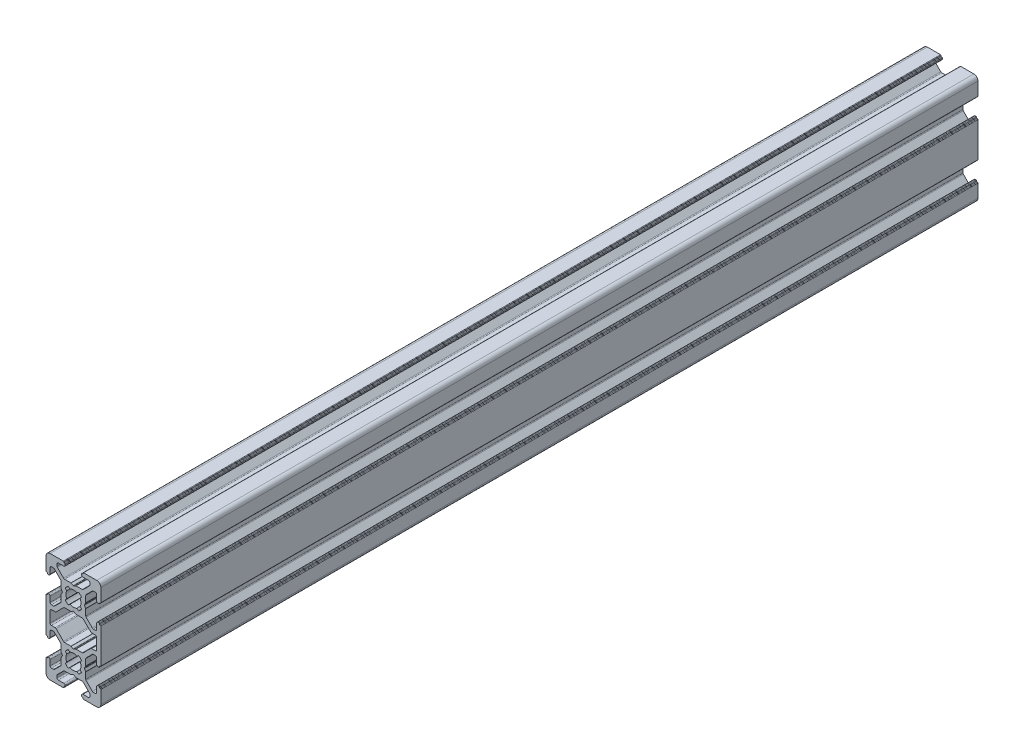
SolidWorks part; units mm, degrees
material "6063-T5"
ref_plane "前视基准面" through (0, 0, 0) normal (0, 0, 1) x (1, 0, 0)
ref_plane "上视基准面" through (0, 0, 0) normal (0, 1, 0) x (1, 0, 0)
ref_plane "右视基准面" through (0, 0, 0) normal (1, 0, 0) x (0, 0, -1)
ref_plane "基准面4" through (0, 0, 10) normal (0, 0, 1) x (1, 0, 0)
sketch "草图1" plane through (0, 0, 10) normal (0, 0, 1) x (1, 0, 0)
  line L0 (2.9477, 1.8871) -> (2.4453, 1.2582)
  line L1 (2.4453, -1.2582) -> (2.9477, -1.8871)
  line L2 (1.8871, -2.9477) -> (1.2582, -2.4453)
  line L3 (-1.2582, -2.4453) -> (-1.8871, -2.9477)
  line L4 (-2.9477, -1.8871) -> (-2.4453, -1.2582)
  line L5 (-2.4453, 1.2582) -> (-2.9477, 1.8871)
  line L6 (-1.8871, 2.9477) -> (-1.2582, 2.4453)
  line L7 (1.2582, 2.4453) -> (1.8871, 2.9477)
  line L8 (2.9477, -18.1129) -> (2.4453, -18.7418)
  line L9 (2.4453, -21.2582) -> (2.9477, -21.8871)
  line L10 (1.8871, -22.9477) -> (1.2582, -22.4453)
  line L11 (-1.2582, -22.4453) -> (-1.8871, -22.9477)
  line L12 (-2.9477, -21.8871) -> (-2.4453, -21.2582)
  line L13 (-2.4453, -18.7418) -> (-2.9477, -18.1129)
  line L14 (-1.8871, -17.0523) -> (-1.2582, -17.5547)
  line L15 (1.2582, -17.5547) -> (1.8871, -17.0523)
  line L16 (-0.9538, -15.4999) -> (-3.2324, -15.4999)
  line L17 (-3.586, -15.3534) -> (-6.2929, -12.6465)
  line L18 (-6.6464, -12.5) -> (-8, -12.5)
  line L19 (-8.5, -12) -> (-8.5, -8)
  line L20 (-8, -7.5) -> (-6.6464, -7.5)
  line L21 (-6.2929, -7.3536) -> (-3.5858, -4.6465)
  line L22 (-3.2322, -4.5) -> (-0.9536, -4.5)
  line L23 (-0.8536, -4.4732) -> (-0.1, -4.0381)
  line L24 (0.1, -4.0381) -> (0.8536, -4.4732)
  line L25 (0.9536, -4.5) -> (3.2322, -4.5)
  line L26 (3.5858, -4.6465) -> (6.2929, -7.3536)
  line L27 (6.6464, -7.5) -> (8, -7.5)
  line L28 (8.5, -8) -> (8.5, -12)
  line L29 (8, -12.5) -> (6.6464, -12.5)
  line L30 (6.2929, -12.6465) -> (3.586, -15.3534)
  line L31 (3.2324, -15.4999) -> (0.9538, -15.4999)
  line L32 (0.8538, -15.5267) -> (0.1, -15.9619)
  line L33 (-0.1, -15.9619) -> (-0.8538, -15.5267)
  line L34 (6, 8) -> (6, 7.2678)
  line L35 (5.8536, 6.9142) -> (3.5859, 4.6465)
  line L36 (3.2323, 4.5) -> (0.9537, 4.5)
  line L37 (0.8537, 4.4733) -> (0.1, 4.0381)
  line L38 (-0.1, 4.0381) -> (-0.8537, 4.4733)
  line L39 (-0.9537, 4.5) -> (-3.2323, 4.5)
  line L40 (-3.5859, 4.6465) -> (-5.8536, 6.9142)
  line L41 (-6, 7.2678) -> (-6, 8)
  line L42 (-5.5, 8.5) -> (-3.5, 8.5)
  line L43 (-3, 9) -> (-3, 9.3)
  line L44 (-3.2, 9.5) -> (-3.3, 9.5)
  line L45 (-3.5, 9.7) -> (-3.5, 9.8)
  line L46 (-3.7, 10) -> (-8.5, 10)
  line L47 (-10, 8.5) -> (-10, 3.7)
  line L48 (-9.8, 3.5) -> (-9.7, 3.5)
  line L49 (-9.5, 3.3) -> (-9.5, 3.2)
  line L50 (-9.3, 3) -> (-9, 3)
  line L51 (-8.5, 3.5) -> (-8.5, 5.55)
  line L52 (-8, 6.05) -> (-7.3178, 6.05)
  line L53 (-6.9642, 5.9036) -> (-4.6464, 3.5858)
  line L54 (-4.5, 3.2322) -> (-4.5, 0.9536)
  line L55 (-4.4732, 0.8536) -> (-4.0381, 0.1)
  line L56 (-4.0381, -0.1) -> (-4.4732, -0.8536)
  line L57 (-4.5, -0.9536) -> (-4.5, -3.2322)
  line L58 (-4.6464, -3.5858) -> (-6.8642, -5.8036)
  line L59 (-7.2178, -5.95) -> (-8, -5.95)
  line L60 (-8.5, -5.45) -> (-8.5, -3.5)
  line L61 (-9, -3) -> (-9.3, -3)
  line L62 (-9.5, -3.2) -> (-9.5, -3.3)
  line L63 (-9.7, -3.5) -> (-9.8, -3.5)
  line L64 (-10, -3.7) -> (-10, -16.35)
  line L65 (-9.8, -16.55) -> (-9.7, -16.55)
  line L66 (-9.5, -16.75) -> (-9.5, -16.85)
  line L67 (-9.3, -17.05) -> (-9, -17.05)
  line L68 (-8.5, -16.55) -> (-8.5, -14.5)
  line L69 (-8, -14) -> (-7.2678, -14)
  line L70 (-6.9142, -14.1464) -> (-4.6464, -16.4142)
  line L71 (-4.5, -16.7678) -> (-4.5, -19.0464)
  line L72 (-4.4732, -19.1464) -> (-4.0381, -19.9)
  line L73 (-4.0381, -20.1) -> (-4.4732, -20.8536)
  line L74 (-4.5, -20.9536) -> (-4.5, -23.2322)
  line L75 (-4.6464, -23.5858) -> (-6.9142, -25.8536)
  line L76 (-7.2678, -26) -> (-8, -26)
  line L77 (-8.5, -25.5) -> (-8.5, -23.55)
  line L78 (-9, -23.05) -> (-9.3, -23.05)
  line L79 (-9.5, -23.25) -> (-9.5, -23.35)
  line L80 (-9.7, -23.55) -> (-9.8, -23.55)
  line L81 (-10, -23.75) -> (-10, -28.5)
  line L82 (-8.5, -30) -> (-3.7, -30)
  line L83 (-3.5, -29.8) -> (-3.5, -29.7)
  line L84 (-3.3, -29.5) -> (-3.2, -29.5)
  line L85 (-3, -29.3) -> (-3, -29)
  line L86 (-3.5, -28.5) -> (-5.5, -28.5)
  line L87 (-6, -28) -> (-6, -27.2678)
  line L88 (-5.8536, -26.9142) -> (-3.5858, -24.6464)
  line L89 (-3.2322, -24.5) -> (-0.9536, -24.5)
  line L90 (-0.8536, -24.4732) -> (-0.1, -24.0381)
  line L91 (0.1, -24.0381) -> (0.8536, -24.4732)
  line L92 (0.9536, -24.5) -> (3.2322, -24.5)
  line L93 (3.5858, -24.6464) -> (5.8536, -26.9142)
  line L94 (6, -27.2678) -> (6, -28)
  line L95 (5.5, -28.5) -> (3.5, -28.5)
  line L96 (3, -29) -> (3, -29.3)
  line L97 (3.2, -29.5) -> (3.3, -29.5)
  line L98 (3.5, -29.7) -> (3.5, -29.8)
  line L99 (3.7, -30) -> (8.5, -30)
  line L100 (10, -28.5) -> (10, -23.75)
  line L101 (9.8, -23.55) -> (9.7, -23.55)
  line L102 (9.5, -23.35) -> (9.5, -23.25)
  line L103 (9.3, -23.05) -> (9, -23.05)
  line L104 (8.5, -23.55) -> (8.5, -25.5)
  line L105 (8, -26) -> (7.2678, -26)
  line L106 (6.9142, -25.8536) -> (4.6464, -23.5858)
  line L107 (4.5, -23.2322) -> (4.5, -20.9536)
  line L108 (4.4732, -20.8536) -> (4.0381, -20.1)
  line L109 (4.0381, -19.9) -> (4.4732, -19.1464)
  line L110 (4.5, -19.0464) -> (4.5, -16.7678)
  line L111 (4.6464, -16.4142) -> (6.9142, -14.1464)
  line L112 (7.2678, -14) -> (8, -14)
  line L113 (8.5, -14.5) -> (8.5, -16.55)
  line L114 (9, -17.05) -> (9.3, -17.05)
  line L115 (9.5, -16.85) -> (9.5, -16.75)
  line L116 (9.7, -16.55) -> (9.8, -16.55)
  line L117 (10, -16.35) -> (10, -3.7)
  line L118 (9.8, -3.5) -> (9.7, -3.5)
  line L119 (9.5, -3.3) -> (9.5, -3.2)
  line L120 (9.3, -3) -> (9, -3)
  line L121 (8.5, -3.5) -> (8.5, -5.5)
  line L122 (8, -6) -> (7.2678, -6)
  line L123 (6.9142, -5.8536) -> (4.6464, -3.5858)
  line L124 (4.5, -3.2322) -> (4.5, -0.9536)
  line L125 (4.4732, -0.8536) -> (4.0381, -0.1)
  line L126 (4.0381, 0.1) -> (4.4732, 0.8536)
  line L127 (4.5, 0.9536) -> (4.5, 3.2322)
  line L128 (4.6464, 3.5858) -> (6.9142, 5.8536)
  line L129 (7.2678, 6) -> (8, 6)
  line L130 (8.5, 5.5) -> (8.5, 3.5)
  line L131 (9, 3) -> (9.3, 3)
  line L132 (9.5, 3.2) -> (9.5, 3.3)
  line L133 (9.7, 3.5) -> (9.8, 3.5)
  line L134 (10, 3.7) -> (10, 8.5)
  line L135 (8.5, 10) -> (3.7, 10)
  line L136 (3.5, 9.8) -> (3.5, 9.7)
  line L137 (3.3, 9.5) -> (3.2, 9.5)
  line L138 (3, 9.3) -> (3, 9)
  line L139 (3.5, 8.5) -> (5.5, 8.5)
  arc A0 (2.4453, 1.2582) -> (2.4453, -1.2582) centre (0, 0) cw
  arc A1 (2.9477, -1.8871) -> (1.8871, -2.9477) centre (0, 0) cw
  arc A2 (1.2582, -2.4453) -> (-1.2582, -2.4453) centre (0, 0) cw
  arc A3 (-1.8871, -2.9477) -> (-2.9477, -1.8871) centre (0, 0) cw
  arc A4 (-2.4453, -1.2582) -> (-2.4453, 1.2582) centre (0, 0) cw
  arc A5 (-2.9477, 1.8871) -> (-1.8871, 2.9477) centre (0, 0) cw
  arc A6 (-1.2582, 2.4453) -> (1.2582, 2.4453) centre (0, 0) cw
  arc A7 (1.8871, 2.9477) -> (2.9477, 1.8871) centre (0, 0) cw
  arc A8 (2.4453, -18.7418) -> (2.4453, -21.2582) centre (0, -20) cw
  arc A9 (2.9477, -21.8871) -> (1.8871, -22.9477) centre (0, -20) cw
  arc A10 (1.2582, -22.4453) -> (-1.2582, -22.4453) centre (0, -20) cw
  arc A11 (-1.8871, -22.9477) -> (-2.9477, -21.8871) centre (0, -20) cw
  arc A12 (-2.4453, -21.2582) -> (-2.4453, -18.7418) centre (0, -20) cw
  arc A13 (-2.9477, -18.1129) -> (-1.8871, -17.0523) centre (0, -20) cw
  arc A14 (-1.2582, -17.5547) -> (1.2582, -17.5547) centre (0, -20) cw
  arc A15 (1.8871, -17.0523) -> (2.9477, -18.1129) centre (0, -20) cw
  arc A16 (-0.8538, -15.5267) -> (-0.9538, -15.4999) centre (-0.9538, -15.6999) ccw
  arc A17 (-3.2324, -15.4999) -> (-3.586, -15.3534) centre (-3.2324, -14.9999) cw
  arc A18 (-6.2929, -12.6465) -> (-6.6464, -12.5) centre (-6.6464, -13) ccw
  arc A19 (-8, -12.5) -> (-8.5, -12) centre (-8, -12) cw
  arc A20 (-8.5, -8) -> (-8, -7.5) centre (-8, -8) cw
  arc A21 (-6.6464, -7.5) -> (-6.2929, -7.3536) centre (-6.6464, -7) ccw
  arc A22 (-3.5858, -4.6465) -> (-3.2322, -4.5) centre (-3.2322, -5) cw
  arc A23 (-0.9536, -4.5) -> (-0.8536, -4.4732) centre (-0.9536, -4.3) ccw
  arc A24 (-0.1, -4.0381) -> (0.1, -4.0381) centre (0, -4.2113) cw
  arc A25 (0.8536, -4.4732) -> (0.9536, -4.5) centre (0.9536, -4.3) ccw
  arc A26 (3.2322, -4.5) -> (3.5858, -4.6465) centre (3.2322, -5) cw
  arc A27 (6.2929, -7.3536) -> (6.6464, -7.5) centre (6.6464, -7) ccw
  arc A28 (8, -7.5) -> (8.5, -8) centre (8, -8) cw
  arc A29 (8.5, -12) -> (8, -12.5) centre (8, -12) cw
  arc A30 (6.6464, -12.5) -> (6.2929, -12.6465) centre (6.6464, -13) ccw
  arc A31 (3.586, -15.3534) -> (3.2324, -15.4999) centre (3.2324, -14.9999) cw
  arc A32 (0.9538, -15.4999) -> (0.8538, -15.5267) centre (0.9538, -15.6999) ccw
  arc A33 (0.1, -15.9619) -> (-0.1, -15.9619) centre (0, -15.7887) cw
  arc A34 (5.5, 8.5) -> (6, 8) centre (5.5, 8) cw
  arc A35 (6, 7.2678) -> (5.8536, 6.9142) centre (5.5, 7.2678) cw
  arc A36 (3.5859, 4.6465) -> (3.2323, 4.5) centre (3.2323, 5) cw
  arc A37 (0.9537, 4.5) -> (0.8537, 4.4733) centre (0.9537, 4.3) ccw
  arc A38 (0.1, 4.0381) -> (-0.1, 4.0381) centre (0, 4.2113) cw
  arc A39 (-0.8537, 4.4733) -> (-0.9537, 4.5) centre (-0.9537, 4.3) ccw
  arc A40 (-3.2323, 4.5) -> (-3.5859, 4.6465) centre (-3.2323, 5) cw
  arc A41 (-5.8536, 6.9142) -> (-6, 7.2678) centre (-5.5, 7.2678) cw
  arc A42 (-6, 8) -> (-5.5, 8.5) centre (-5.5, 8) cw
  arc A43 (-3.5, 8.5) -> (-3, 9) centre (-3.5, 9) ccw
  arc A44 (-3, 9.3) -> (-3.2, 9.5) centre (-3.2, 9.3) ccw
  arc A45 (-3.3, 9.5) -> (-3.5, 9.7) centre (-3.3, 9.7) cw
  arc A46 (-3.5, 9.8) -> (-3.7, 10) centre (-3.7, 9.8) ccw
  arc A47 (-8.5, 10) -> (-10, 8.5) centre (-8.5, 8.5) ccw
  arc A48 (-10, 3.7) -> (-9.8, 3.5) centre (-9.8, 3.7) ccw
  arc A49 (-9.7, 3.5) -> (-9.5, 3.3) centre (-9.7, 3.3) cw
  arc A50 (-9.5, 3.2) -> (-9.3, 3) centre (-9.3, 3.2) ccw
  arc A51 (-9, 3) -> (-8.5, 3.5) centre (-9, 3.5) ccw
  arc A52 (-8.5, 5.55) -> (-8, 6.05) centre (-8, 5.55) cw
  arc A53 (-7.3178, 6.05) -> (-6.9642, 5.9036) centre (-7.3178, 5.55) cw
  arc A54 (-4.6464, 3.5858) -> (-4.5, 3.2322) centre (-5, 3.2322) cw
  arc A55 (-4.5, 0.9536) -> (-4.4732, 0.8536) centre (-4.3, 0.9536) ccw
  arc A56 (-4.0381, 0.1) -> (-4.0381, -0.1) centre (-4.2113, 0) cw
  arc A57 (-4.4732, -0.8536) -> (-4.5, -0.9536) centre (-4.3, -0.9536) ccw
  arc A58 (-4.5, -3.2322) -> (-4.6464, -3.5858) centre (-5, -3.2322) cw
  arc A59 (-6.8642, -5.8036) -> (-7.2178, -5.95) centre (-7.2178, -5.45) cw
  arc A60 (-8, -5.95) -> (-8.5, -5.45) centre (-8, -5.45) cw
  arc A61 (-8.5, -3.5) -> (-9, -3) centre (-9, -3.5) ccw
  arc A62 (-9.3, -3) -> (-9.5, -3.2) centre (-9.3, -3.2) ccw
  arc A63 (-9.5, -3.3) -> (-9.7, -3.5) centre (-9.7, -3.3) cw
  arc A64 (-9.8, -3.5) -> (-10, -3.7) centre (-9.8, -3.7) ccw
  arc A65 (-10, -16.35) -> (-9.8, -16.55) centre (-9.8, -16.35) ccw
  arc A66 (-9.7, -16.55) -> (-9.5, -16.75) centre (-9.7, -16.75) cw
  arc A67 (-9.5, -16.85) -> (-9.3, -17.05) centre (-9.3, -16.85) ccw
  arc A68 (-9, -17.05) -> (-8.5, -16.55) centre (-9, -16.55) ccw
  arc A69 (-8.5, -14.5) -> (-8, -14) centre (-8, -14.5) cw
  arc A70 (-7.2678, -14) -> (-6.9142, -14.1464) centre (-7.2678, -14.5) cw
  arc A71 (-4.6464, -16.4142) -> (-4.5, -16.7678) centre (-5, -16.7678) cw
  arc A72 (-4.5, -19.0464) -> (-4.4732, -19.1464) centre (-4.3, -19.0464) ccw
  arc A73 (-4.0381, -19.9) -> (-4.0381, -20.1) centre (-4.2113, -20) cw
  arc A74 (-4.4732, -20.8536) -> (-4.5, -20.9536) centre (-4.3, -20.9536) ccw
  arc A75 (-4.5, -23.2322) -> (-4.6464, -23.5858) centre (-5, -23.2322) cw
  arc A76 (-6.9142, -25.8536) -> (-7.2678, -26) centre (-7.2678, -25.5) cw
  arc A77 (-8, -26) -> (-8.5, -25.5) centre (-8, -25.5) cw
  arc A78 (-8.5, -23.55) -> (-9, -23.05) centre (-9, -23.55) ccw
  arc A79 (-9.3, -23.05) -> (-9.5, -23.25) centre (-9.3, -23.25) ccw
  arc A80 (-9.5, -23.35) -> (-9.7, -23.55) centre (-9.7, -23.35) cw
  arc A81 (-9.8, -23.55) -> (-10, -23.75) centre (-9.8, -23.75) ccw
  arc A82 (-10, -28.5) -> (-8.5, -30) centre (-8.5, -28.5) ccw
  arc A83 (-3.7, -30) -> (-3.5, -29.8) centre (-3.7, -29.8) ccw
  arc A84 (-3.5, -29.7) -> (-3.3, -29.5) centre (-3.3, -29.7) cw
  arc A85 (-3.2, -29.5) -> (-3, -29.3) centre (-3.2, -29.3) ccw
  arc A86 (-3, -29) -> (-3.5, -28.5) centre (-3.5, -29) ccw
  arc A87 (-5.5, -28.5) -> (-6, -28) centre (-5.5, -28) cw
  arc A88 (-6, -27.2678) -> (-5.8536, -26.9142) centre (-5.5, -27.2678) cw
  arc A89 (-3.5858, -24.6464) -> (-3.2322, -24.5) centre (-3.2322, -25) cw
  arc A90 (-0.9536, -24.5) -> (-0.8536, -24.4732) centre (-0.9536, -24.3) ccw
  arc A91 (-0.1, -24.0381) -> (0.1, -24.0381) centre (0, -24.2113) cw
  arc A92 (0.8536, -24.4732) -> (0.9536, -24.5) centre (0.9536, -24.3) ccw
  arc A93 (3.2322, -24.5) -> (3.5858, -24.6464) centre (3.2322, -25) cw
  arc A94 (5.8536, -26.9142) -> (6, -27.2678) centre (5.5, -27.2678) cw
  arc A95 (6, -28) -> (5.5, -28.5) centre (5.5, -28) cw
  arc A96 (3.5, -28.5) -> (3, -29) centre (3.5, -29) ccw
  arc A97 (3, -29.3) -> (3.2, -29.5) centre (3.2, -29.3) ccw
  arc A98 (3.3, -29.5) -> (3.5, -29.7) centre (3.3, -29.7) cw
  arc A99 (3.5, -29.8) -> (3.7, -30) centre (3.7, -29.8) ccw
  arc A100 (8.5, -30) -> (10, -28.5) centre (8.5, -28.5) ccw
  arc A101 (10, -23.75) -> (9.8, -23.55) centre (9.8, -23.75) ccw
  arc A102 (9.7, -23.55) -> (9.5, -23.35) centre (9.7, -23.35) cw
  arc A103 (9.5, -23.25) -> (9.3, -23.05) centre (9.3, -23.25) ccw
  arc A104 (9, -23.05) -> (8.5, -23.55) centre (9, -23.55) ccw
  arc A105 (8.5, -25.5) -> (8, -26) centre (8, -25.5) cw
  arc A106 (7.2678, -26) -> (6.9142, -25.8536) centre (7.2678, -25.5) cw
  arc A107 (4.6464, -23.5858) -> (4.5, -23.2322) centre (5, -23.2322) cw
  arc A108 (4.5, -20.9536) -> (4.4732, -20.8536) centre (4.3, -20.9536) ccw
  arc A109 (4.0381, -20.1) -> (4.0381, -19.9) centre (4.2113, -20) cw
  arc A110 (4.4732, -19.1464) -> (4.5, -19.0464) centre (4.3, -19.0464) ccw
  arc A111 (4.5, -16.7678) -> (4.6464, -16.4142) centre (5, -16.7678) cw
  arc A112 (6.9142, -14.1464) -> (7.2678, -14) centre (7.2678, -14.5) cw
  arc A113 (8, -14) -> (8.5, -14.5) centre (8, -14.5) cw
  arc A114 (8.5, -16.55) -> (9, -17.05) centre (9, -16.55) ccw
  arc A115 (9.3, -17.05) -> (9.5, -16.85) centre (9.3, -16.85) ccw
  arc A116 (9.5, -16.75) -> (9.7, -16.55) centre (9.7, -16.75) cw
  arc A117 (9.8, -16.55) -> (10, -16.35) centre (9.8, -16.35) ccw
  arc A118 (10, -3.7) -> (9.8, -3.5) centre (9.8, -3.7) ccw
  arc A119 (9.7, -3.5) -> (9.5, -3.3) centre (9.7, -3.3) cw
  arc A120 (9.5, -3.2) -> (9.3, -3) centre (9.3, -3.2) ccw
  arc A121 (9, -3) -> (8.5, -3.5) centre (9, -3.5) ccw
  arc A122 (8.5, -5.5) -> (8, -6) centre (8, -5.5) cw
  arc A123 (7.2678, -6) -> (6.9142, -5.8536) centre (7.2678, -5.5) cw
  arc A124 (4.6464, -3.5858) -> (4.5, -3.2322) centre (5, -3.2322) cw
  arc A125 (4.5, -0.9536) -> (4.4732, -0.8536) centre (4.3, -0.9536) ccw
  arc A126 (4.0381, -0.1) -> (4.0381, 0.1) centre (4.2113, 0) cw
  arc A127 (4.4732, 0.8536) -> (4.5, 0.9536) centre (4.3, 0.9536) ccw
  arc A128 (4.5, 3.2322) -> (4.6464, 3.5858) centre (5, 3.2322) cw
  arc A129 (6.9142, 5.8536) -> (7.2678, 6) centre (7.2678, 5.5) cw
  arc A130 (8, 6) -> (8.5, 5.5) centre (8, 5.5) cw
  arc A131 (8.5, 3.5) -> (9, 3) centre (9, 3.5) ccw
  arc A132 (9.3, 3) -> (9.5, 3.2) centre (9.3, 3.2) ccw
  arc A133 (9.5, 3.3) -> (9.7, 3.5) centre (9.7, 3.3) cw
  arc A134 (9.8, 3.5) -> (10, 3.7) centre (9.8, 3.7) ccw
  arc A135 (10, 8.5) -> (8.5, 10) centre (8.5, 8.5) ccw
  arc A136 (3.7, 10) -> (3.5, 9.8) centre (3.7, 9.8) ccw
  arc A137 (3.5, 9.7) -> (3.3, 9.5) centre (3.3, 9.7) cw
  arc A138 (3.2, 9.5) -> (3, 9.3) centre (3.2, 9.3) ccw
  arc A139 (3, 9) -> (3.5, 8.5) centre (3.5, 9) ccw
extrude "凸台-拉伸1" add sketch "草图1" against normal blind 320
